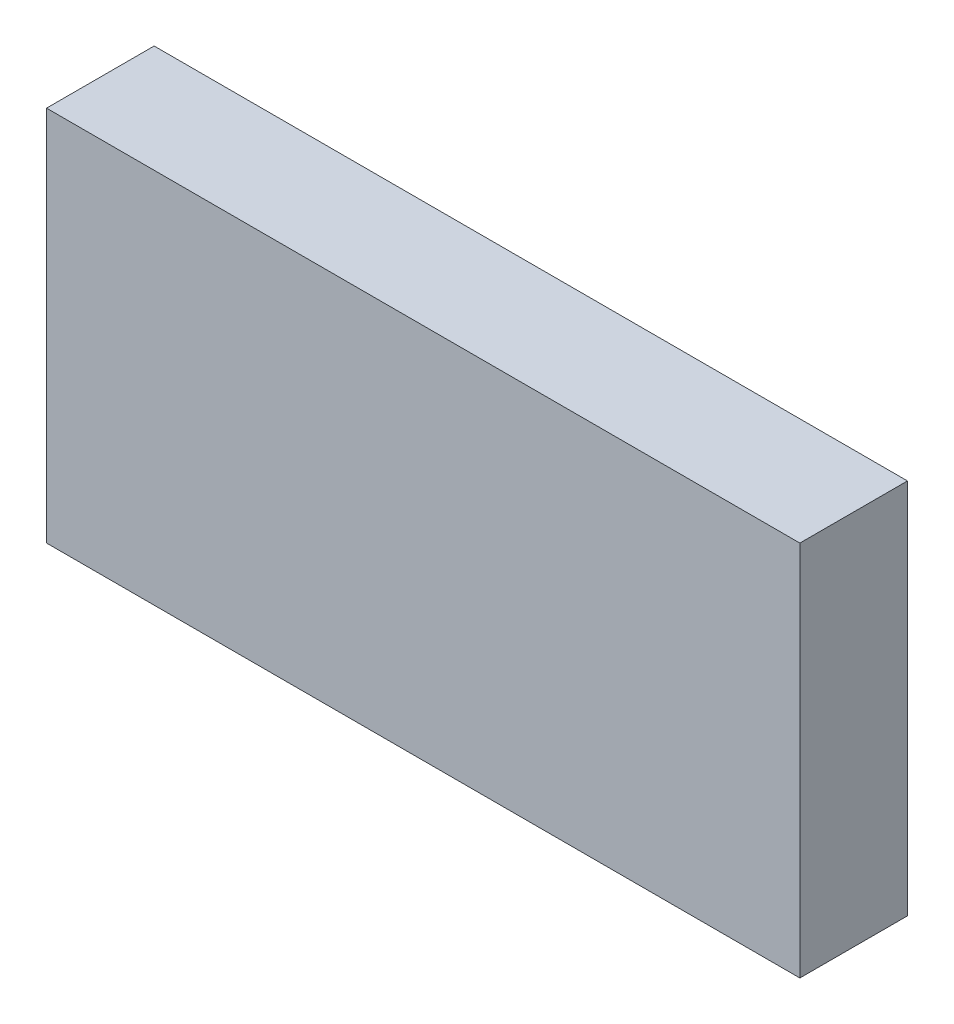
SolidWorks part; units mm, degrees
ref_plane "前视基准面" through (0, 0, 0) normal (0, 0, 1) x (1, 0, 0)
ref_plane "上视基准面" through (0, 0, 0) normal (0, 1, 0) x (1, 0, 0)
ref_plane "右视基准面" through (0, 0, 0) normal (1, 0, 0) x (0, 0, -1)
other "Configuration Table"
sketch "草图1" plane through (0, 0, 0) normal (0, 0, 1) x (1, 0, 0)
  line L1 (-70, -35) -> (70, -35)
  line L2 (-70, -35) -> (-70, 35)
  line L3 (-70, 35) -> (70, 35)
  line L4 (70, -35) -> (70, 35)
  line L5 (-70, -35) -> (70, 35) construction
  line L6 (-70, 35) -> (70, -35) construction
  point P0 (0, 0)
extrude "凸台-拉伸1" add sketch "草图1" along normal blind 20
